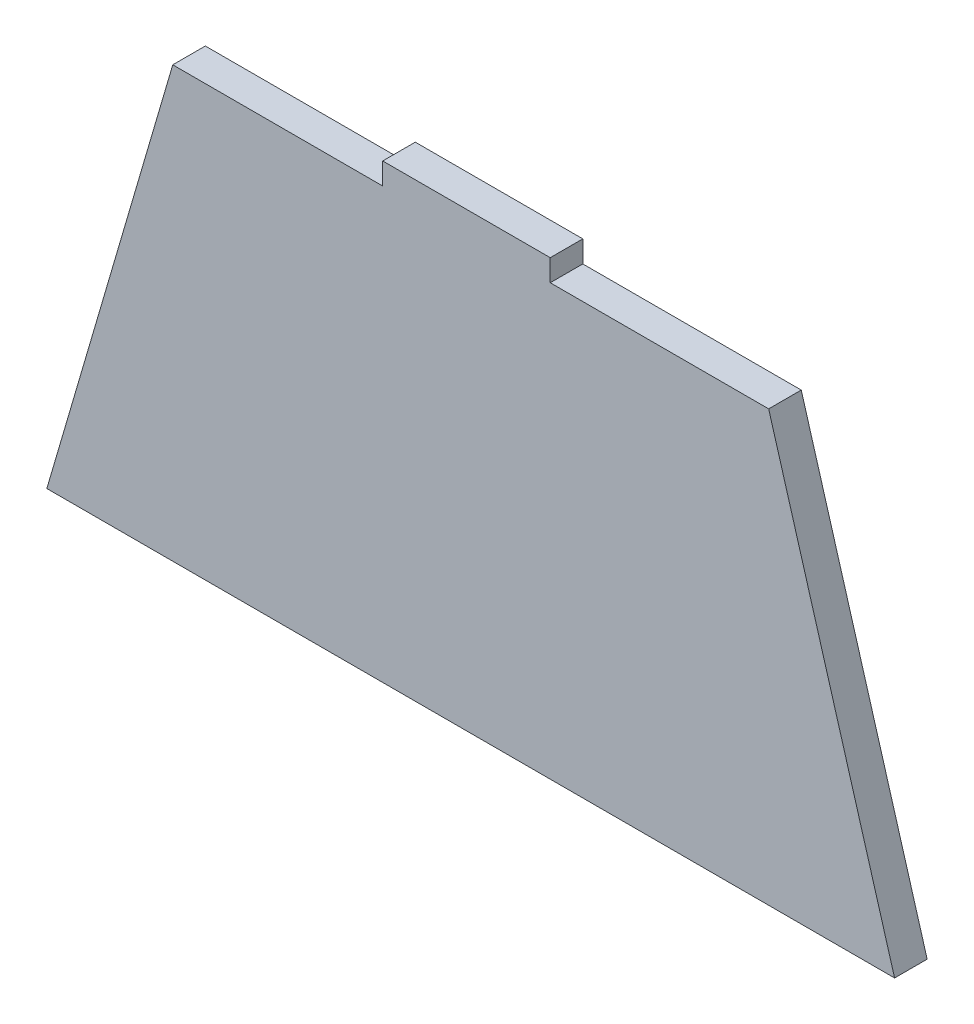
SolidWorks part; units mm, degrees
ref_plane "Front" through (0, 0, 0) normal (0, 0, 1) x (1, 0, 0)
ref_plane "Top" through (0, 0, 0) normal (0, 1, 0) x (1, 0, 0)
ref_plane "Right" through (0, 0, 0) normal (1, 0, 0) x (0, 0, -1)
sketch "Sketch1" plane through (0, 0, 0) normal (0, 0, 1) x (1, 0, 0)
  line L0 (-211.493, 138.6328) -> (-248.3167, 12.9104)
  line L1 (-248.3167, 12.9104) -> (-0.4127, 12.9104)
  line L2 (-0.4127, 12.9104) -> (-37.2363, 138.6328)
  line L3 (-37.2363, 138.6328) -> (-101.111, 138.6328)
  line L4 (-150.0995, 138.6328) -> (-150.0995, 144.9828)
  line L5 (-150.0995, 144.9828) -> (-101.111, 144.9828)
  line L6 (-101.111, 144.9828) -> (-101.111, 138.6328)
  line L7 (-150.0995, 138.6328) -> (-211.493, 138.6328)
  dimension "D1" = 174.2567
  dimension "D2" = 247.904
  dimension "D3" = 125.7224
  dimension "D4" = 6.35
extrude "Boss-Extrude1" add sketch "Sketch1" against normal blind 9.525
